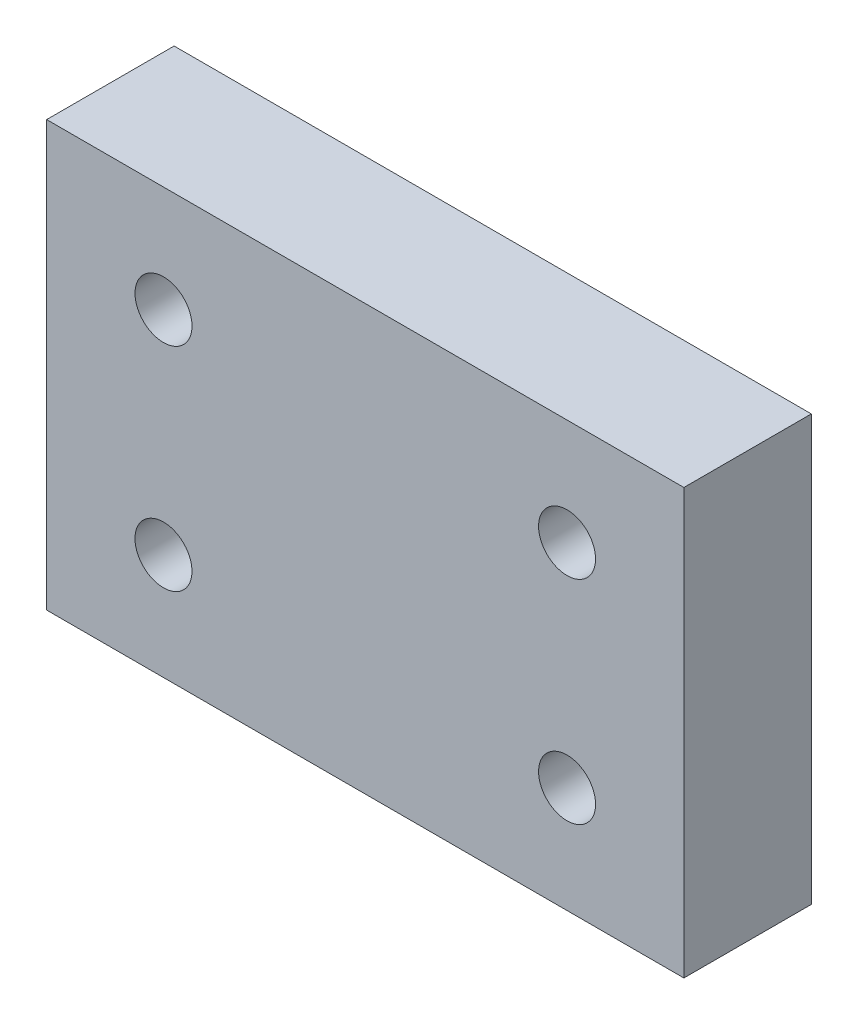
SolidWorks part; units mm, degrees
ref_plane "Plan de face" through (0, 0, 0) normal (0, 0, 1) x (1, 0, 0)
ref_plane "Plan de dessus" through (0, 0, 0) normal (0, 1, 0) x (1, 0, 0)
ref_plane "Plan de droite" through (0, 0, 0) normal (1, 0, 0) x (0, 0, -1)
sketch "Esquisse1" plane through (0, 0, 0) normal (0, 0, 1) x (1, 0, 0)
  line L0 (15, 20) -> (15, 0) construction
  line L1 (0, 0) -> (30, 0)
  line L2 (0, 0) -> (0, 20)
  line L3 (0, 20) -> (30, 20)
  line L4 (30, 0) -> (30, 20)
  line L5 (0, 10) -> (30, 10) construction
  circle A0 centre (5.5, 15) radius 1.3418
  circle A1 centre (24.5, 15) radius 1.3418
  circle A2 centre (24.5, 5) radius 1.3418
  circle A3 centre (5.5, 5) radius 1.3418
  dimension "D1" = 30
  dimension "D2" = 20
  dimension "D3" = 5
  dimension "D4" = 5.5
extrude "Boss.-Extru.1" add sketch "Esquisse1" along normal blind 6
